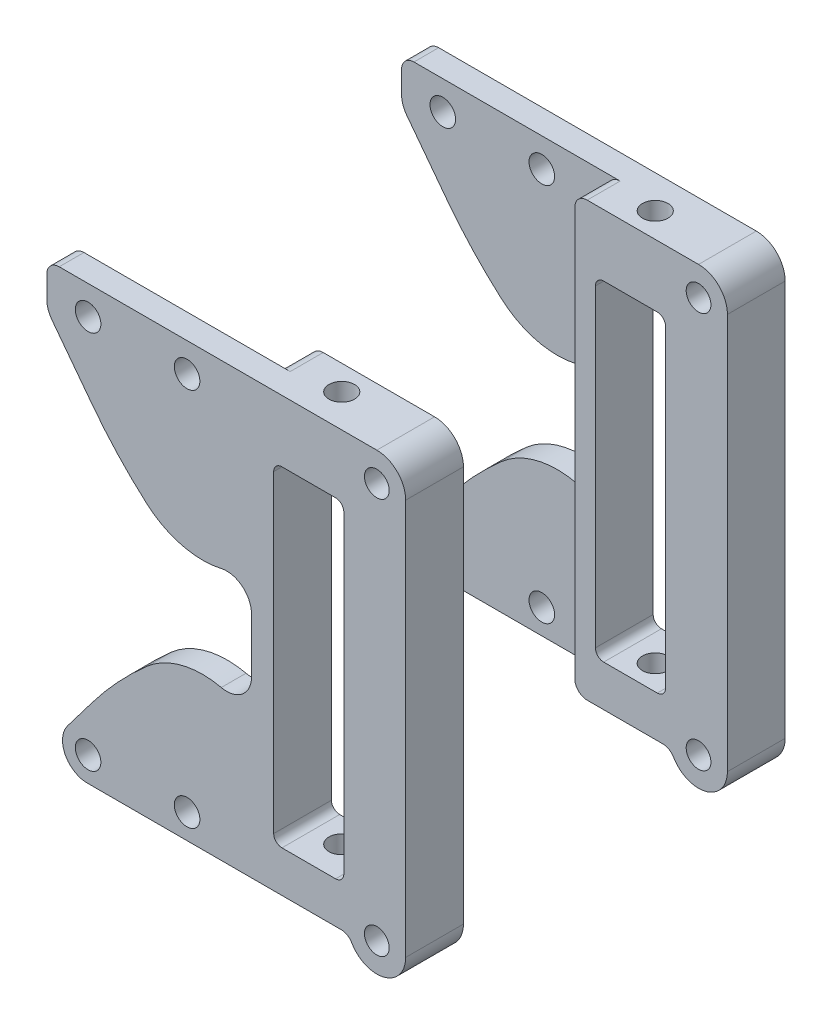
SolidWorks part; units mm, degrees
material "6061-T6 (SS)"
ref_plane "前视基准面" through (0, 0, 0) normal (0, 0, 1) x (1, 0, 0)
ref_plane "上视基准面" through (0, 0, 0) normal (0, 1, 0) x (1, 0, 0)
ref_plane "右视基准面" through (0, 0, 0) normal (1, 0, 0) x (0, 0, -1)
sketch "草图1" plane through (0, 0, 0) normal (0, 0, 1) x (1, 0, 0)
  line L0 (-30, -29) -> (30, -29)
  line L1 (-30, -30) -> (30, -30)
  line L2 (-30, -30) -> (-30, 30)
  line L3 (-30, 30) -> (30, 30)
  line L4 (30, -30) -> (30, 30)
  line L5 (-30, -30) -> (30, 30) construction
  line L6 (-30, 30) -> (30, -30) construction
  line L7 (0, 15) -> (60, 15)
  line L8 (0, 15) -> (0, -25)
  line L9 (0, -25) -> (60, -25)
  line L10 (60, 15) -> (60, -25)
  line L11 (0, 15) -> (60, -25) construction
  line L12 (0, -25) -> (60, 15) construction
  line L13 (-30, 29) -> (30, 29)
  line L14 (-30, 28.5) -> (30, 28.5)
  line L15 (0, 14.5) -> (60, 14.5)
  line L16 (-30, 26.1) -> (30, 26.1)
  point P0 (0, 0)
  point P6 (30, -5)
  dimension "D1" = 60
  dimension "D2" = 60
  dimension "D3" = 5
  dimension "D4" = 40
  dimension "D5" = 60
  dimension "D6" = 1
  dimension "D7" = 1
  dimension "D8" = 0.5
  dimension "D9" = 14
  dimension "D10" = 2.4
sketch "草图3" plane through (0, 0, 0) normal (0, 0, 1) x (1, 0, 0)
  line L0 (0, 15) -> (60, 15) construction
  line L1 (30, -30) -> (30, 30) construction
  line L2 (45, 22.5) -> (5, 22.5)
  line L3 (5, 22.5) -> (5, -30)
  line L4 (-30, -30) -> (30, -30) construction
  line L5 (0, -25) -> (60, -25) construction
  line L6 (5, -30) -> (41.6459, -30)
  line L7 (48.5, -29) -> (48.5, 19)
  line L8 (30, 19) -> (5, 19) construction
  line L9 (-30, 30) -> (30, 30) construction
  line L10 (5, -27) -> (30, -27) construction
  circle A0 centre (45, 19) radius 4 construction
  circle A1 centre (45, 19) radius 1.5
  circle A2 centre (45, 19) radius 3.5 construction
  circle A3 centre (45, -29) radius 1.5
  circle A4 centre (45, -29) radius 4 construction
  circle A5 centre (45, -29) radius 3.5 construction
  arc A6 (45, 22.5) -> (48.5, 19) centre (45, 19) cw
  arc A7 (48.5, -29) -> (41.6459, -30) centre (45, -29) cw
  circle A8 centre (22, 19) radius 1.55
  circle A9 centre (10, 19) radius 1.55
  circle A10 centre (10, -27) radius 1.55
  circle A11 centre (22, -27) radius 1.55
  circle A12 centre (10, -21) radius 1.25 construction
  circle A13 centre (22, -21) radius 1.25 construction
  circle A14 centre (10, -1) radius 1.25 construction
  circle A15 centre (22, -1) radius 1.25 construction
  dimension "D1" = 8
  dimension "D2" = 3
  dimension "D3" = 15
  dimension "D4" = 7
  dimension "D5" = 8
  dimension "D6" = 3
  dimension "D7" = 7
  dimension "D10" = 8
  dimension "D11" = 12
  dimension "D12" = 3.1
  dimension "D13" = 3.1
  dimension "D15" = 3.1
  dimension "D16" = 3.1
  dimension "D17" = 2.5
  dimension "D18" = 20
  dimension "D19" = 20
  dimension "D8" = 25
  dimension "D9" = 11
  dimension "D14" = 3
extrude "凸台-拉伸1" add sketch "草图3" along normal blind 3
sketch "草图4" plane through (0, 0, 3) normal (0, 0, 1) x (1, 0, 0)
  line L0 (30, 22.5) -> (30, -30)
  line L1 (30, -30) -> (30, 30) construction
  line L2 (45, 22.5) -> (5, 22.5) construction
  line L3 (30, -30) -> (41.6459, -30)
  line L4 (48.5, -29) -> (48.5, 19)
  line L5 (30, 22.5) -> (45, 22.5)
  arc A0 (48.5, -29) -> (41.6459, -30) centre (45, -29) cw
  arc A1 (45, 22.5) -> (48.5, 19) centre (45, 19) cw
  circle A2 centre (45, 19) radius 1.5
  circle A3 centre (45, -29) radius 1.5
  dimension "D1" = 3
  dimension "D2" = 3
extrude "凸台-拉伸2" add sketch "草图4" along normal blind 4
sketch "草图5" plane through (0, 0, 7) normal (0, 0, 1) x (1, 0, 0)
  line L0 (30, -30) -> (30, 30) construction
  line L1 (32.5, 15) -> (41, 15)
  line L2 (32.5, 15) -> (32.5, -25)
  line L3 (32.5, -25) -> (41, -25)
  line L4 (41, 15) -> (41, -25)
  line L7 (0, 15) -> (60, 15) construction
  line L8 (0, -25) -> (60, -25) construction
  dimension "D1" = 2.5
  dimension "D3" = 8.5
extrude "切除-拉伸1" cut sketch "草图5" against normal blind 17
sketch "草图7" plane through (0, 22.5, 0) normal (0, 1, 0) x (1, 0, 0)
  line L0 (30, -7) -> (30, -3) construction
  line L1 (0, 0) -> (60, 0) construction
  circle A0 centre (36.75, -4) radius 1.55
  dimension "D1" = 6.75
  dimension "D2" = 4
  dimension "D3" = 3.1
extrude "切除-拉伸2" cut sketch "草图7" against normal blind 57
fillet "圆角1" radius 1 4 edges at (41, 15, 3.5) (41, -25, 3.5) (32.5, -25, 3.5) (32.5, 15, 3.5)
fillet "圆角2" radius 1.5 5 edges at (41.6459, -30, 3.5) (5, -30, 1.5) (5, 22.5, 1.5) (30, 22.5, 5) (30, -30, 5)
ref_plane "基准面4" through (0, 0, 23) normal (0, 0, 1) x (1, 0, 0)
sketch "草图8" plane through (0, 0, 3) normal (0, 0, 1) x (1, 0, 0)
  line L0 (29.8093, -13.4764) -> (29.8093, 2.2762)
  line L1 (10.4964, -21.2495) -> (5, -28.5)
  line L2 (20.1932, 0.4504) -> (5.3046, 20.0939) construction
  line L3 (29.8093, -5.6001) -> (5, -5.6001) construction
  line L4 (5, 21) -> (5, -28.5) construction
  line L5 (5.3046, 20.0939) -> (5, -28.5) construction
  line L6 (5.3046, 20.0939) -> (2.6922, 23.5406) construction
  line L7 (10.4964, 10.0493) -> (5, 17.2998)
  line L8 (2.6922, 23.5406) -> (2.6922, -31.5443) construction
  line L9 (2.6922, -31.5443) -> (5, -28.5)
  line L10 (5, 17.2998) -> (2.6922, 20.3441)
  line L11 (2.6922, 20.3441) -> (2.6922, -31.5443)
  arc A0 (29.8093, 2.2762) -> (20.1932, 0.4504) centre (24.5479, 3.751) cw construction
  arc A1 (6.5, 22.5) -> (5, 21) centre (6.5, 21) ccw construction
  arc A2 (17.1233, -14.1348) -> (29.8093, -13.4764) centre (23.8837, -21.8486) cw
  arc A3 (10.4964, -21.2495) -> (17.1233, -14.1348) centre (48.8198, -50.3015) cw
  arc A4 (10.4964, 10.0493) -> (17.1233, 2.9346) centre (48.8198, 39.1013) ccw
  arc A5 (17.1233, 2.9346) -> (29.8093, 2.2762) centre (23.8837, 10.6484) ccw
extrude "切除-拉伸3" cut sketch "草图8" against normal through all
fillet "圆角3" radius 3 4 edges at (5, -28.5, 1.5) (29.8093, -13.4764, 1.5) (5, 17.2998, 1.5) (29.8093, 2.2762, 1.5)
mirror "镜向1" about plane through (0, 0, 23) normal (0, 0, 1) of bodies 108 104
